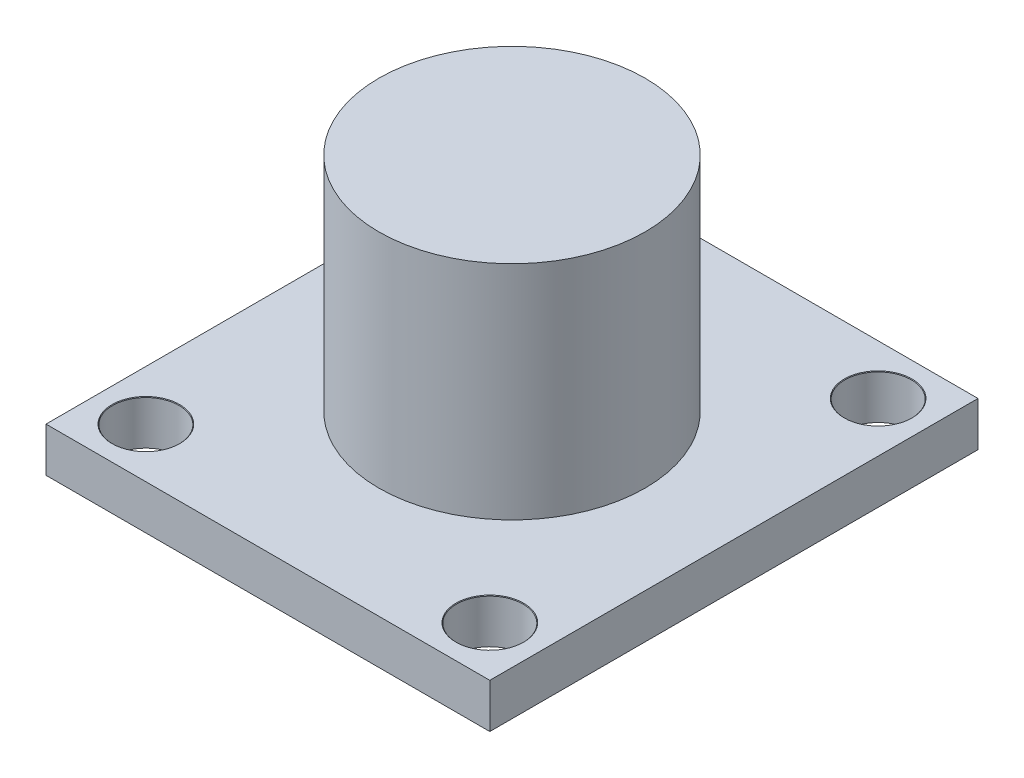
SolidWorks part; units mm, degrees
ref_plane "Front Plane" through (0, 0, 0) normal (0, 0, 1) x (1, 0, 0)
ref_plane "Top Plane" through (0, 0, 0) normal (0, 1, 0) x (1, 0, 0)
ref_plane "Right Plane" through (0, 0, 0) normal (1, 0, 0) x (0, 0, -1)
sketch "Sketch1" plane through (0, 0, 0) normal (0, 1, 0) x (1, 0, 0)
  line L1 (-10, 11) -> (10, 11)
  line L2 (-10, 11) -> (-10, -11)
  line L3 (-10, -11) -> (10, -11)
  line L4 (10, 11) -> (10, -11)
  line L5 (-10, 11) -> (10, -11) construction
  line L6 (-10, -11) -> (10, 11) construction
  point P0 (0, 0)
  dimension "D1" = 20
  dimension "D2" = 22
extrude "Boss-Extrude1" add sketch "Sketch1" along normal blind 2
hole_wizard "Ø3.0 (3) Diameter Hole1" positions "Sketch2" profile "Sketch3" hole size "Ø3.0" standard "ISO" end condition through all
sketch "Sketch2" plane through (0, 2, 0) normal (0, 1, 0) x (1, 0, 0)
  line L1 (-7.75, 8.75) -> (7.75, 8.75)
  line L2 (-7.75, 8.75) -> (-7.75, -8.75)
  line L3 (-7.75, -8.75) -> (7.75, -8.75)
  line L4 (7.75, 8.75) -> (7.75, -8.75)
  line L5 (0, 0) -> (0, -8.75) construction
  line L7 (0, 0) -> (7.75, 0) construction
  point P2 (-7.75, 8.75)
  point P3 (7.75, -8.75)
  point P94 (-7.75, -8.75)
  point P95 (7.75, 8.75)
  point P114 (8.6383, 8.75)
  point P115 (0, 0)
  dimension "D1" = 15.5
  dimension "D2" = 17.5
sketch "Sketch3" plane through (-7.75, 2, -8.75) normal (1, 0, 0) x (0, 0, 1)
  line L0 (0, 0) -> (0, 2)
  line L1 (0, 2) -> (1.5, 2)
  line L2 (1.5, 2) -> (1.5, 0.025)
  line L3 (1.5, 0.025) -> (1.525, 0)
  line L5 (1.525, 0) -> (0, 0)
  line L6 (-1.5, 0.025) -> (-1.525, 0) construction
  line L11 (0, -6.35) -> (0, 107.95) construction
  dimension "Thru Hole Dia." = 3
  dimension "Thru Hole Depth" = 2
  dimension "Near C'Sink Dia." = 3.05
  dimension "Near C'Sink Angle" = 90
sketch "Sketch4" plane through (0, 2, 0) normal (0, 1, 0) x (1, 0, 0)
  circle A0 centre (0, 0) radius 6
  dimension "D1" = 12
extrude "Boss-Extrude2" add sketch "Sketch4" along normal blind 10
